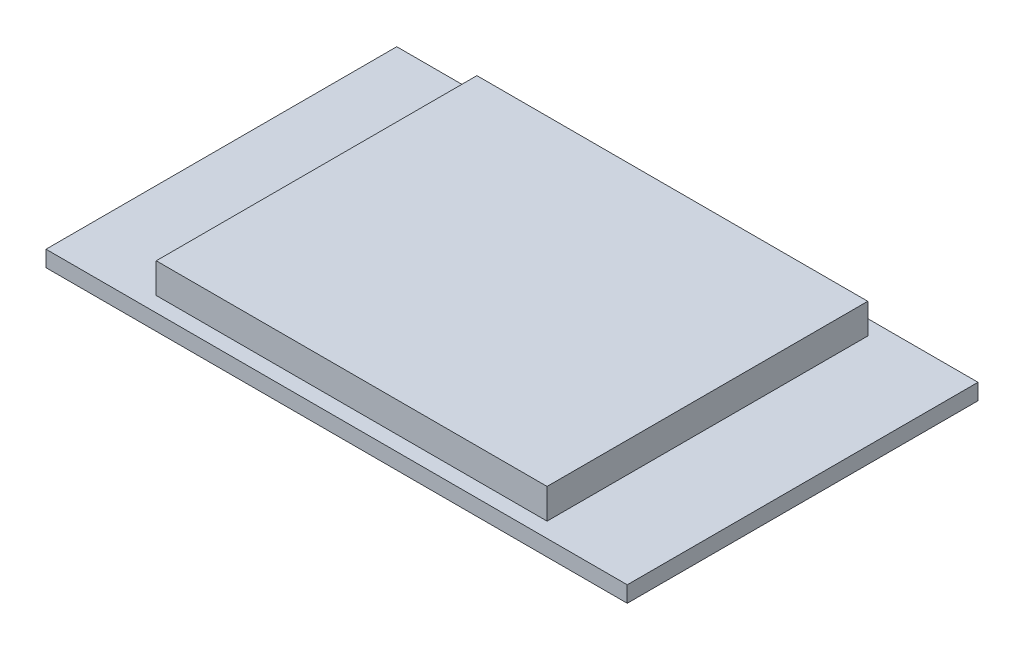
SolidWorks part; units mm, degrees
ref_plane "Front Plane" through (0, 0, 0) normal (0, 0, 1) x (1, 0, 0)
ref_plane "Top Plane" through (0, 0, 0) normal (0, 1, 0) x (1, 0, 0)
ref_plane "Right Plane" through (0, 0, 0) normal (1, 0, 0) x (0, 0, -1)
other "Configuration Table"
sketch "Sketch1" plane through (0, 0, 0) normal (0, 1, 0) x (1, 0, 0)
  line L0 (-19.5, -16) -> (19.5, -16)
  line L1 (19.5, -16) -> (19.5, 16)
  line L2 (19.5, 16) -> (-19.5, 16)
  line L3 (-19.5, 16) -> (-19.5, -16)
extrude "LCD_Glass" add sketch "Sketch1" along normal blind 3 from offset 3
sketch "Sketch2" plane through (0, 0, 0) normal (0, 1, 0) x (1, 0, 0)
  line L1 (-29, -17.5) -> (29, -17.5)
  line L2 (-29, -17.5) -> (-29, 17.5)
  line L3 (-29, 17.5) -> (29, 17.5)
  line L4 (29, -17.5) -> (29, 17.5)
  line L5 (-29, -17.5) -> (29, 17.5) construction
  line L6 (-29, 17.5) -> (29, -17.5) construction
  point P6 (0, 0)
  dimension "D1" = 58
  dimension "D2" = 35
extrude "Board" add sketch "Sketch2" along normal blind 1.6 from offset 4.6
equation "\"Jar_OD\"= 90  'ASSUMED - Part G fallback - jar outer diameter"
equation "\"Jar_H\"= 120  'ASSUMED - Part G fallback - jar height"
equation "\"Pump_L\"= 45  'ASSUMED - Part G fallback"
equation "\"Pump_W\"= 24  'ASSUMED - Part G fallback"
equation "\"Pump_H\"= 33  'ASSUMED - Part G fallback"
equation "\"Pump_Outlet_OD\"= 7.5  'ASSUMED - Part G fallback"
equation "\"Tube_OD\"= 8  'ASSUMED - Part G fallback"
equation "\"Tube_ID\"= 6  'ASSUMED - Part G fallback"
equation "\"TDS_Body_Dia\"= 12  'ASSUMED - Part G fallback"
equation "\"TDS_Wet_Len\"= 45  'ASSUMED - Part G fallback - length in water"
equation "\"DS_Tube_Dia\"= 6  'ASSUMED - Part G fallback"
equation "\"DS_Tube_Len\"= 50  'ASSUMED - Part G fallback"
equation "\"ORP_Body_Dia\"= 12  'ASSUMED - Part G fallback"
equation "\"ORP_Body_Len\"= 150  'ASSUMED - Part G fallback"
equation "\"ORP_Cap_Dia\"= 16  'ASSUMED - Part G fallback"
equation "\"Turb_W\"= 33  'ASSUMED - Part G fallback - head width"
equation "\"Turb_D\"= 28  'ASSUMED - Part G fallback - head depth"
equation "\"Turb_H\"= 30  'ASSUMED - Part G fallback - head height"
equation "\"Turb_Slot_W\"= 10  'ASSUMED - Part G fallback - slot width"
equation "\"Flow_L\"= 62  'ASSUMED - Part G fallback YF-S201"
equation "\"Flow_W\"= 36  'ASSUMED - Part G fallback"
equation "\"Flow_H\"= 35  'ASSUMED - Part G fallback"
equation "\"Thread_G12_OD\"= 20.955  'ASSUMED - Part G fallback thread G1/2 (major diameter)"
equation "\"Valve_L\"= 75  'ASSUMED - Part G fallback"
equation "\"Valve_W\"= 45  'ASSUMED - Part G fallback"
equation "\"Valve_H\"= 60  'ASSUMED - Part G fallback"
equation "\"Tee_L\"= 40  'ASSUMED - Part G fallback - overall length"
equation "\"Tee_Branch_L\"= 25  'ASSUMED - Part G fallback"
equation "\"Tee_OD\"= 12  'ASSUMED - Part G fallback"
equation "\"Cuv_W\"= 12.5  'ASSUMED - old R3 cuvette (station suppressed in SS4)"
equation "\"Cuv_D\"= 12.5  'ASSUMED - old R3 cuvette (station suppressed in SS4)"
equation "\"Cuv_H\"= 45  'ASSUMED - old R3 cuvette (station suppressed in SS4)"
equation "\"LED_Board_L\"= 20  'ASSUMED - Part G fallback"
equation "\"LED_Board_W\"= 20  'ASSUMED - Part G fallback - LED at centre"
equation "\"GUVA_L\"= 20  'ASSUMED - Part G fallback"
equation "\"GUVA_W\"= 12  'ASSUMED - Part G fallback - sensor at centre"
equation "\"Reed_L\"= 27  'ASSUMED - Part G fallback MC-38 half"
equation "\"Reed_W\"= 14  'ASSUMED - Part G fallback"
equation "\"Reed_H\"= 8  'ASSUMED - Part G fallback"
equation "\"ESP_L\"= 51  'ASSUMED - Part G fallback"
equation "\"ESP_W\"= 28  'ASSUMED - Part G fallback"
equation "\"TFT_L\"= 58  'ASSUMED - Part G fallback - board"
equation "\"TFT_W\"= 35  'ASSUMED - Part G fallback - board"
equation "\"TFT_Win_L\"= 35  'ASSUMED - Part G fallback - visible window"
equation "\"TFT_Win_W\"= 28  'ASSUMED - Part G fallback - visible window"
equation "\"Relay_L\"= 50  'ASSUMED - Part G fallback"
equation "\"Relay_W\"= 26  'ASSUMED - Part G fallback"
equation "\"Relay_H\"= 19  'ASSUMED - Part G fallback"
equation "\"Mosfet_L\"= 34  'ASSUMED - Part G fallback"
equation "\"Mosfet_W\"= 17  'ASSUMED - Part G fallback"
equation "\"Mosfet_H\"= 12  'ASSUMED - Part G fallback"
equation "\"TDS_Board_L\"= 42  'ASSUMED - Part G fallback"
equation "\"TDS_Board_W\"= 32  'ASSUMED - Part G fallback"
equation "\"Turb_Board_L\"= 38  'ASSUMED - Part G fallback"
equation "\"Turb_Board_W\"= 28  'ASSUMED - Part G fallback"
equation "\"BNC_Thread_Dia\"= 9.5  'ASSUMED - Part G fallback"
equation "\"Plate_L\"= 420  'ASSUMED - Part G fallback"
equation "\"Plate_W\"= 297  'ASSUMED - Part G fallback"
equation "\"Plate_T\"= 6  'ASSUMED - Part G fallback"
equation "\"Probe_Clr\"= 0.3  'DESIGN VALUE - Part C rule 3 - printed probe hole = diameter + 0.3"
equation "\"Cuv_Clr\"= 0.2  'DESIGN VALUE - Part C rule 3 - cuvette pocket = size + 0.2"
equation "\"Label_H\"= 0.6  'DESIGN VALUE - Part D - raised label height"
equation "\"D1@Sketch2\" = \"TFT_L\""
equation "\"D2@Sketch2\" = \"TFT_W\""
equation "\"Booster_L\"= 150  'ASSUMED - Part G fallback - booster pump"
equation "\"Booster_W\"= 95  'ASSUMED - Part G fallback"
equation "\"Booster_H\"= 100  'ASSUMED - Part G fallback"
equation "\"PTube_OD\"= 6.35  'ASSUMED - Part G fallback - product tube 1/4 inch"
equation "\"Qz_Out\"= 12  'ASSUMED - Part G fallback - quartz channel outside square"
equation "\"Qz_Path\"= 10  'ASSUMED - Part G fallback - quartz channel inside light path"
equation "\"Qz_L\"= 40  'ASSUMED - Part G fallback - quartz channel length"
equation "\"LED860_Dia\"= 5  'ASSUMED - Part G fallback - 860 nm LED"
equation "\"BPW_L\"= 5.4  'ASSUMED - Part G fallback - BPW34"
equation "\"BPW_W\"= 4.3  'ASSUMED - Part G fallback - BPW34"
equation "\"Cart_Dia\"= 50  'ASSUMED - Part G fallback - sediment and pre-carbon cartridges"
equation "\"Cart_L\"= 255  'ASSUMED - Part G fallback"
equation "\"UF_Dia\"= 50  'ASSUMED - Part G fallback - UF cartridge"
equation "\"UF_L\"= 260  'ASSUMED - Part G fallback"
equation "\"RO_Dia\"= 62  'ASSUMED - Part G fallback - RO membrane housing"
equation "\"RO_L\"= 300  'ASSUMED - Part G fallback"
equation "\"UVC_Dia\"= 40  'ASSUMED - Part G fallback - UV-C chamber"
equation "\"UVC_L\"= 300  'ASSUMED - Part G fallback"
equation "\"Tank_W\"= 260  'ASSUMED - Part G fallback - storage tank"
equation "\"Tank_D\"= 160  'ASSUMED - Part G fallback"
equation "\"Tank_H\"= 300  'ASSUMED - Part G fallback"
equation "\"Cab_W\"= 400  'ASSUMED - Part G fallback - purifier cabinet"
equation "\"Cab_D\"= 270  'ASSUMED - Part G fallback"
equation "\"Cab_H\"= 560  'ASSUMED - Part G fallback"
equation "\"ORP_Board_L\"= 40  'ASSUMED - Part G fallback - ORP buffer board"
equation "\"ORP_Board_W\"= 30  'ASSUMED - Part G fallback"
equation "\"Opt_Board_L\"= 50  'ASSUMED - Part G fallback - optical front-end board"
equation "\"Opt_Board_W\"= 40  'ASSUMED - Part G fallback"
equation "\"Buck_L\"= 43  'ASSUMED - Part G fallback - 12 V to 5 V buck module"
equation "\"Buck_W\"= 21  'ASSUMED - Part G fallback"
equation "\"Buck_H\"= 14  'ASSUMED - Part G fallback"
equation "\"BB_L\"= 165  'ASSUMED - Part G fallback - breadboard (As_Built_R3 only)"
equation "\"BB_W\"= 55  'ASSUMED - Part G fallback"
equation "\"BB_H\"= 10  'ASSUMED - Part G fallback"
